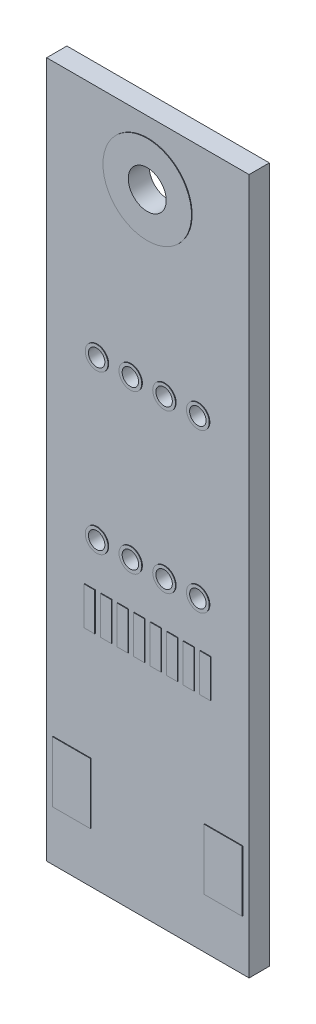
SolidWorks part; units mm, degrees
ref_plane "Front Plane" through (0, 0, 0) normal (0, 0, 1) x (1, 0, 0)
ref_plane "Top Plane" through (0, 0, 0) normal (0, 1, 0) x (1, 0, 0)
ref_plane "Right Plane" through (0, 0, 0) normal (1, 0, 0) x (0, 0, -1)
sketch "Sketch1" plane through (0, 0, 0) normal (0, 0, 1) x (1, 0, 0)
  line L1 (-8, -27.5) -> (8, -27.5)
  line L2 (-8, -27.5) -> (-8, 27.5)
  line L3 (-8, 27.5) -> (8, 27.5)
  line L4 (8, -27.5) -> (8, 27.5)
  line L5 (-8, -27.5) -> (8, 27.5) construction
  line L6 (-8, 27.5) -> (8, -27.5) construction
  circle A0 centre (0, 22.5) radius 1.5
  point P0 (0, 0)
  dimension "D3" = 3
  dimension "D4" = 5
  dimension "D5" = 8
  dimension "D1" = 16
  dimension "D2" = 55
extrude "Boss-Extrude1" add sketch "Sketch1" along normal blind 1.6
sketch "Sketch3" plane through (0, 0, 1.6) normal (0, 0, 1) x (1, 0, 0)
  line L0 (-8, 27.5) -> (-8, -27.5) construction
  line L1 (8, -27.5) -> (8, 27.5) construction
  line L2 (8, 27.5) -> (-8, 27.5) construction
  circle A0 centre (-4, -3.5) radius 0.65
  circle A1 centre (-1.3333, -3.5) radius 0.65
  circle A2 centre (1.3333, -3.5) radius 0.65
  circle A3 centre (4, -3.5) radius 0.65
  circle A4 centre (-4, 9) radius 0.65
  circle A5 centre (-1.3333, 9) radius 0.65
  circle A6 centre (1.3333, 9) radius 0.65
  circle A7 centre (4, 9) radius 0.65
  dimension "D1" = 1.3
  dimension "D2" = 4
  dimension "D4" = 4
  dimension "D5" = 31
  dimension "D3" = 4
  dimension "D6" = 2
extrude "Cut-Extrude1" cut sketch "Sketch3" against normal through all
sketch "Sketch4" plane through (0, 0, 1.6) normal (0, 0, 1) x (1, 0, 0)
  line L0 (-8, 27.5) -> (-8, -27.5) construction
  line L1 (-5, -7) -> (-4.15, -7)
  line L2 (-5, -7) -> (-5, -10)
  line L3 (-5, -10) -> (-4.15, -10)
  line L4 (-4.15, -7) -> (-4.15, -10)
  line L5 (-3.6929, -7) -> (-3.6929, -10)
  line L6 (-3.6929, -7) -> (-2.8429, -7)
  line L7 (-2.8429, -7) -> (-2.8429, -10)
  line L8 (-3.6929, -10) -> (-2.8429, -10)
  line L9 (-2.3857, -7) -> (-2.3857, -10)
  line L10 (-2.3857, -7) -> (-1.5357, -7)
  line L11 (-1.5357, -7) -> (-1.5357, -10)
  line L12 (-2.3857, -10) -> (-1.5357, -10)
  line L13 (-1.0786, -7) -> (-1.0786, -10)
  line L14 (-1.0786, -7) -> (-0.2286, -7)
  line L15 (-0.2286, -7) -> (-0.2286, -10)
  line L16 (-1.0786, -10) -> (-0.2286, -10)
  line L17 (0.2286, -7) -> (0.2286, -10)
  line L18 (0.2286, -7) -> (1.0786, -7)
  line L19 (1.0786, -7) -> (1.0786, -10)
  line L20 (0.2286, -10) -> (1.0786, -10)
  line L21 (1.5357, -7) -> (1.5357, -10)
  line L22 (1.5357, -7) -> (2.3857, -7)
  line L23 (2.3857, -7) -> (2.3857, -10)
  line L24 (1.5357, -10) -> (2.3857, -10)
  line L25 (2.8429, -7) -> (2.8429, -10)
  line L26 (2.8429, -7) -> (3.6929, -7)
  line L27 (3.6929, -7) -> (3.6929, -10)
  line L28 (2.8429, -10) -> (3.6929, -10)
  line L29 (4.15, -7) -> (4.15, -10)
  line L30 (4.15, -7) -> (5, -7)
  line L31 (5, -7) -> (5, -10)
  line L32 (4.15, -10) -> (5, -10)
  line L33 (8, -27.5) -> (8, 27.5) construction
  line L34 (-8, -27.5) -> (8, -27.5) construction
  line L35 (-7.5, -18.7) -> (-4.5, -18.7)
  line L36 (-7.5, -18.7) -> (-7.5, -23.5)
  line L37 (-7.5, -23.5) -> (-4.5, -23.5)
  line L38 (-4.5, -18.7) -> (-4.5, -23.5)
  line L39 (0, -27.5) -> (0, -25.7482) construction
  line L40 (7.5, -18.7) -> (7.5, -23.5)
  line L41 (7.5, -23.5) -> (4.5, -23.5)
  line L42 (4.5, -18.7) -> (4.5, -23.5)
  line L43 (7.5, -18.7) -> (4.5, -18.7)
  circle A0 centre (-4, -3.5) radius 0.65 construction
  circle A4 centre (-4, 9) radius 0.9
  circle A5 centre (-4, -3.5) radius 0.65
  circle A6 centre (-4, -3.5) radius 0.65
  circle A7 centre (-1.3333, -3.5) radius 0.65
  circle A8 centre (-1.3333, -3.5) radius 0.65
  circle A9 centre (1.3333, -3.5) radius 0.65
  circle A10 centre (1.3333, -3.5) radius 0.65
  circle A11 centre (4, -3.5) radius 0.65
  circle A12 centre (4, -3.5) radius 0.65
  circle A13 centre (4, 9) radius 0.65
  circle A14 centre (4, 9) radius 0.65
  circle A15 centre (1.3333, 9) radius 0.65
  circle A16 centre (1.3333, 9) radius 0.65
  circle A17 centre (-1.3333, 9) radius 0.65
  circle A18 centre (-1.3333, 9) radius 0.65
  circle A19 centre (-4, 9) radius 0.65
  circle A20 centre (-4, 9) radius 0.65
  circle A21 centre (0, 22.5) radius 1.5
  circle A22 centre (0, 22.5) radius 1.5
  circle A23 centre (-1.3333, 9) radius 0.9
  circle A24 centre (1.3333, 9) radius 0.9
  circle A25 centre (4, 9) radius 0.9
  circle A26 centre (4, -3.5) radius 0.9
  circle A27 centre (1.3333, -3.5) radius 0.9
  circle A28 centre (-1.3333, -3.5) radius 0.9
  circle A29 centre (-4, -3.5) radius 0.9
  circle A30 centre (0, 22.5) radius 3.5
  dimension "D1" = 3
  dimension "D2" = 0.85
  dimension "D3" = 3
  dimension "D4" = 3.5
  dimension "D6" = 3
  dimension "D7" = 4.8
  dimension "D8" = 3
  dimension "D9" = 4
  dimension "D10" = 0.5
  dimension "D11" = 0
  dimension "D12" = 0
  dimension "D13" = 17.5
  dimension "D14" = 0
  dimension "D15" = 0
  dimension "D16" = 0
  dimension "D17" = 0
  dimension "D18" = 0
  dimension "D19" = 0
  dimension "D20" = 0
  dimension "D21" = 0.25
  dimension "D22" = 2
  dimension "D5" = 8
extrude "Boss-Extrude3" add sketch "Sketch4" along normal blind 0.05
